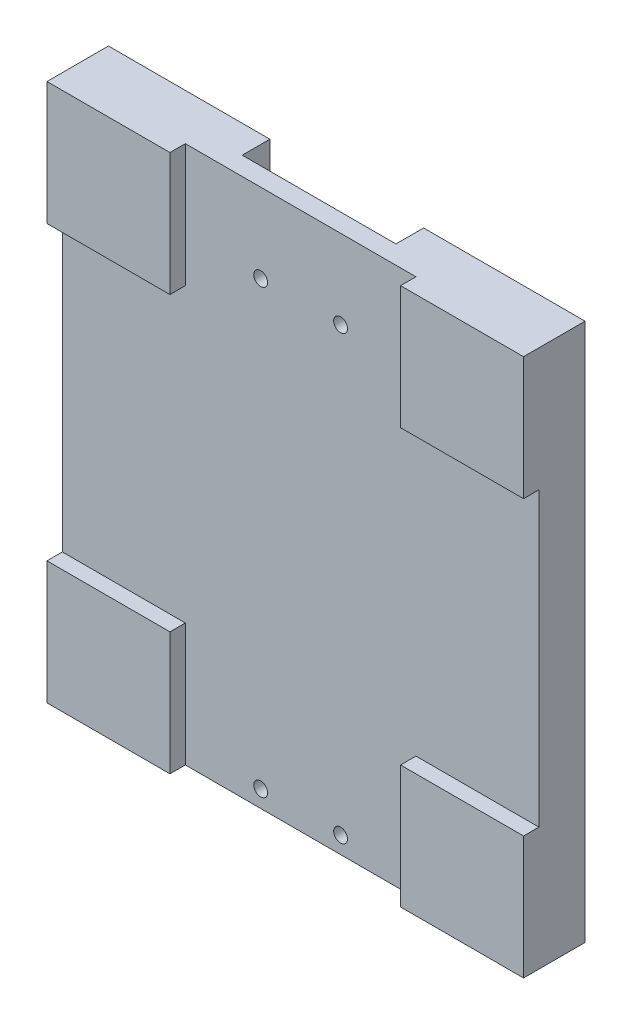
SolidWorks part; units mm, degrees
ref_plane "前视基准面" through (0, 0, 0) normal (0, 0, 1) x (1, 0, 0)
ref_plane "上视基准面" through (0, 0, 0) normal (0, 1, 0) x (1, 0, 0)
ref_plane "右视基准面" through (0, 0, 0) normal (1, 0, 0) x (0, 0, -1)
other "Configuration Table"
sketch "草图1" plane through (0, 0, 0) normal (0, 0, 1) x (1, 0, 0)
  line L5 (155, -175) -> (-155, -175)
  line L6 (155, -175) -> (155, 175)
  line L7 (155, 175) -> (-155, 175)
  line L8 (-155, -175) -> (-155, 175)
  line L9 (155, -175) -> (-155, 175) construction
  line L10 (155, 175) -> (-155, -175) construction
  point P0 (0, 0)
  dimension "D1" = 350
  dimension "D2" = 310
extrude "凸台-拉伸1" add sketch "草图1" along normal blind 30
sketch "草图2" plane through (0, 175, 0) normal (0, 1, 0) x (1, 0, 0)
  line L0 (-50, 0) -> (-50, -18)
  line L1 (155, 0) -> (-155, 0) construction
  line L2 (-50, -18) -> (50, -18)
  line L3 (50, -18) -> (50, 0)
  line L4 (-50, 0) -> (50, 0)
  line L5 (0, 0) -> (0, -18) construction
  dimension "D1" = 18
  dimension "D2" = 100
extrude "切除-拉伸1" cut sketch "草图2" against normal through all
sketch "草图3" plane through (0, 0, 30) normal (0, 0, 1) x (1, 0, 0)
  line L1 (-155, 175) -> (-75, 175)
  line L2 (-155, 175) -> (-155, 95)
  line L3 (-155, 95) -> (-75, 95)
  line L4 (-75, 175) -> (-75, 95)
  line L5 (155, 175) -> (75, 175)
  line L6 (155, 175) -> (155, 95)
  line L7 (155, 95) -> (75, 95)
  line L8 (75, 175) -> (75, 95)
  line L9 (-155, -175) -> (-75, -175)
  line L10 (-155, -175) -> (-155, -95)
  line L11 (-155, -95) -> (-75, -95)
  line L12 (-75, -175) -> (-75, -95)
  line L13 (155, -175) -> (75, -175)
  line L14 (155, -175) -> (155, -95)
  line L15 (155, -95) -> (75, -95)
  line L16 (75, -175) -> (75, -95)
  dimension "D1" = 80
  dimension "D2" = 80
  dimension "D3" = 80
  dimension "D4" = 80
  dimension "D5" = 80
  dimension "D6" = 80
  dimension "D7" = 80
  dimension "D8" = 80
extrude "凸台-拉伸2" add sketch "草图3" along normal blind 10
sketch "草图5" plane through (0, -175, 0) normal (0, -1, 0) x (1, 0, 0)
  line L0 (0, 30) -> (0, 7.9651) construction
  line L5 (-50, 18) -> (50, 18) construction
  line L6 (-75, 30) -> (75, 30) construction
  line L7 (-35.5, 18) -> (35.5, 18)
  line L8 (-35.5, 18) -> (-35.5, 22)
  line L9 (-35.5, 22) -> (35.5, 22)
  line L10 (35.5, 18) -> (35.5, 22)
  dimension "D1" = 71
  dimension "D2" = 4
extrude "切除-拉伸3" cut sketch "草图5" against normal blind 21
sketch "草图7" plane through (0, 0, 18) normal (0, 0, -1) x (-1, 0, 0)
  line L0 (50, 175) -> (-50, 175) construction
  line L1 (-35.5, 135.5) -> (35.5, 135.5)
  line L2 (-35.5, 135.5) -> (-35.5, 110.5)
  line L3 (-35.5, 110.5) -> (35.5, 110.5)
  line L4 (35.5, 135.5) -> (35.5, 110.5)
  line L5 (0, 175) -> (0, 175.9816) construction
  dimension "D1" = 71
  dimension "D2" = 25
  dimension "D3" = 39.5
extrude "切除-拉伸4" cut sketch "草图7" against normal blind 4
sketch "草图8" plane through (0, 0, 18) normal (0, 0, -1) x (-1, 0, 0)
  circle A0 centre (-26, 123.5) radius 4.5
  circle A1 centre (26, 123.5) radius 4.5
  circle A2 centre (-26, -164) radius 4.5
  circle A3 centre (26, -164) radius 4.5
extrude "切除-拉伸5" cut sketch "草图8" against normal through all
sketch "草图9" plane through (0, 0, 0) normal (0, 0, -1) x (-1, 0, 0)
  line L0 (0, 0) -> (165.2281, 0) construction
  line L1 (0, 0) -> (0, 79.8445) construction
  circle A0 centre (-147, 144) radius 3
  circle A1 centre (-101, 144) radius 3
  circle A2 centre (101, 144) radius 3
  circle A3 centre (147, 144) radius 3
  circle A4 centre (147, -144) radius 3
  circle A5 centre (101, -144) radius 3
  circle A6 centre (-101, -144) radius 3
  circle A7 centre (-147, -144) radius 3
  dimension "D1" = 6
hole_wizard "M6 螺纹孔1" positions "3D草图1" profile "草图10" tap size "M6" standard "GB"
sketch3d "3D草图1"
  point P0 (147, 144, 0)
  point P3 (101, 144, 0)
  point P6 (-101, 144, 0)
  point P9 (-147, 144, 0)
  point P12 (147, -144, 0)
  point P15 (101, -144, 0)
  point P18 (-101, -144, 0)
  point P21 (-147, -144, 0)
sketch "草图10" plane through (147, 144, 0) normal (1, 0, 0) x (0, 1, 0)
  line L0 (0, 0) -> (0, 13.5022)
  line L1 (0, 13.5022) -> (2.5, 12)
  line L2 (2.5, 12) -> (2.5, 0)
  line L5 (2.5, 0) -> (0, 0)
  line L10 (0, 13.5022) -> (-2.5, 12) construction
  line L11 (0, -6.35) -> (0, 107.95) construction
  dimension "螺纹孔钻头直径" = 5
  dimension "螺纹孔钻头深度" = 12
  dimension "导头角度" = 118
cosmetic thread "孔螺蚊线1" parameters "D1"=12, "D2"=6
cosmetic thread "孔螺蚊线2" parameters "D1"=12, "D2"=6
cosmetic thread "孔螺蚊线3" parameters "D1"=12, "D2"=6
cosmetic thread "孔螺蚊线4" parameters "D1"=12, "D2"=6
cosmetic thread "孔螺蚊线5" parameters "D1"=12, "D2"=6
cosmetic thread "孔螺蚊线6" parameters "D1"=12, "D2"=6
cosmetic thread "孔螺蚊线7" parameters "D1"=12, "D2"=6
cosmetic thread "孔螺蚊线8" parameters "D1"=12, "D2"=6
sketch "草图13" plane through (0, 0, 0) normal (0, 0, -1) x (-1, 0, 0)
  circle A0 centre (-82.5, 150) radius 2.25
  circle A1 centre (82.5, 150) radius 2.25
hole_wizard "M4 螺纹孔1" positions "3D草图4" profile "草图14" tap size "M4" standard "GB"
sketch3d "3D草图4"
  point P0 (82.5, 150, 0)
  point P3 (-82.5, 150, 0)
sketch "草图14" plane through (82.5, 150, 0) normal (1, 0, 0) x (0, 1, 0)
  line L0 (0, 0) -> (0, 10.9914)
  line L1 (0, 10.9914) -> (1.65, 10)
  line L2 (1.65, 10) -> (1.65, 0)
  line L5 (1.65, 0) -> (0, 0)
  line L10 (0, 10.9914) -> (-1.65, 10) construction
  line L11 (0, -6.35) -> (0, 107.95) construction
  dimension "螺纹孔钻头直径" = 3.3
  dimension "螺纹孔钻头深度" = 10
  dimension "导头角度" = 118
cosmetic thread "孔螺蚊线9" parameters "D1"=8, "D2"=4
cosmetic thread "孔螺蚊线10" parameters "D1"=8, "D2"=4
pattern_linear "阵列(线性)1" count 6 spacing 60 along (0, -1, 0) of "M4 螺纹孔1"
